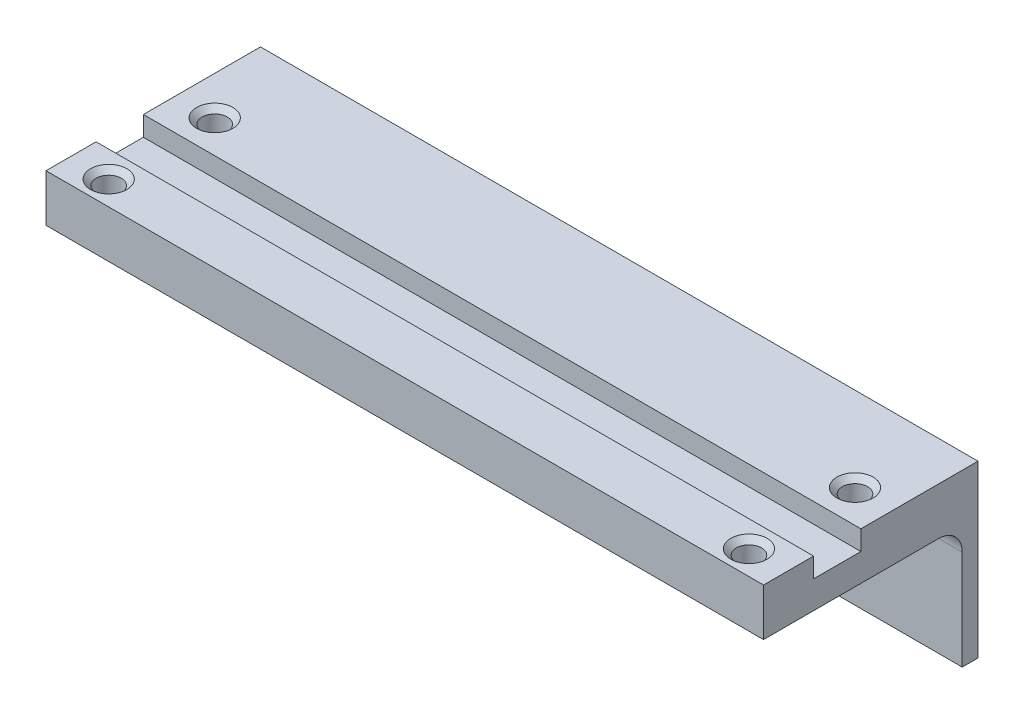
SolidWorks part; units mm, degrees
ref_plane "Front Plane" through (0, 0, 0) normal (0, 0, 1) x (1, 0, 0)
ref_plane "Top Plane" through (0, 0, 0) normal (0, 1, 0) x (1, 0, 0)
ref_plane "Right Plane" through (0, 0, 0) normal (1, 0, 0) x (0, 0, -1)
sketch "Sketch1" plane through (0, 0, 0) normal (0, 1, 0) x (1, 0, 0)
  line L5 (-45.5, 12) -> (45.5, 12)
  line L6 (-45.5, 12) -> (-45.5, -12)
  line L7 (-45.5, -12) -> (45.5, -12)
  line L8 (45.5, 12) -> (45.5, -12)
  line L9 (-45.5, 12) -> (45.5, -12) construction
  line L10 (-45.5, -12) -> (45.5, 12) construction
  point P0 (0, 0)
  dimension "D1" = 91
  dimension "D2" = 24
extrude "Boss-Extrude1" add sketch "Sketch1" along normal blind 4
sketch "Sketch2" plane through (0, 4, 0) normal (0, 1, 0) x (1, 0, 0)
  circle A0 centre (-40.6, 3.5) radius 1.6
  circle A2 centre (-40.6, -9.95) radius 1.6
  circle A3 centre (40.6, 3.5) radius 1.6
  circle A4 centre (40.6, -9.95) radius 1.6
  line B0 (-42.6, 12) -> (-42.6, -12)
  line B1 (-42.6, -12) -> (42.6, -12)
  line B2 (42.6, -12) -> (42.6, 12)
  line B3 (42.6, 12) -> (-42.6, 12)
  line B4 (-42.6, 0) -> (42.6, 0) construction
  line B5 (0, 12) -> (0, -12) construction
  arc B6 (41.75, -9.95) -> (39.45, -9.95) centre (40.6, -9.95) ccw
  arc B7 (39.45, -9.95) -> (41.75, -9.95) centre (40.6, -9.95) ccw
  arc B8 (41.75, 3.5) -> (39.45, 3.5) centre (40.6, 3.5) ccw
  arc B9 (39.45, 3.5) -> (41.75, 3.5) centre (40.6, 3.5) ccw
  arc B10 (11.65, 3.5) -> (9.35, 3.5) centre (10.5, 3.5) ccw
  arc B11 (9.35, 3.5) -> (11.65, 3.5) centre (10.5, 3.5) ccw
  arc B12 (11.65, -9.95) -> (9.35, -9.95) centre (10.5, -9.95) ccw
  arc B13 (9.35, -9.95) -> (11.65, -9.95) centre (10.5, -9.95) ccw
  arc B14 (-39.45, -9.95) -> (-41.75, -9.95) centre (-40.6, -9.95) ccw
  arc B15 (-41.75, -9.95) -> (-39.45, -9.95) centre (-40.6, -9.95) ccw
  arc B16 (-39.45, 3.5) -> (-41.75, 3.5) centre (-40.6, 3.5) ccw
  arc B17 (-41.75, 3.5) -> (-39.45, 3.5) centre (-40.6, 3.5) ccw
  arc B18 (-22.05, -3.65) -> (-20.55, -3.65) centre (-21.3, -3.65) ccw
  arc B19 (-20.55, -3.65) -> (-22.05, -3.65) centre (-21.3, -3.65) ccw
  arc B20 (-9.35, -9.95) -> (-11.65, -9.95) centre (-10.5, -9.95) ccw
  arc B21 (-11.65, -9.95) -> (-9.35, -9.95) centre (-10.5, -9.95) ccw
  arc B22 (20.55, -3.65) -> (22.05, -3.65) centre (21.3, -3.65) ccw
  arc B23 (22.05, -3.65) -> (20.55, -3.65) centre (21.3, -3.65) ccw
  arc B24 (-39.55, -3.65) -> (-38.05, -3.65) centre (-38.8, -3.65) ccw
  arc B25 (-38.05, -3.65) -> (-39.55, -3.65) centre (-38.8, -3.65) ccw
  arc B26 (38.05, -3.65) -> (39.55, -3.65) centre (38.8, -3.65) ccw
  arc B27 (39.55, -3.65) -> (38.05, -3.65) centre (38.8, -3.65) ccw
  arc B28 (-11.65, 3.5) -> (-9.35, 3.5) centre (-10.5, 3.5) ccw
  arc B29 (-9.35, 3.5) -> (-11.65, 3.5) centre (-10.5, 3.5) ccw
  dimension "D1" = 3.2
  dimension "D2" = 3.2
  dimension "D3" = 3.2
  dimension "D4" = 3.2
sketch_block_instance "Block2-2"
sketch_block "Block2"
extrude "Cut-Extrude1" cut sketch "Sketch2" against normal through all contours A2 | A4 | A0 | A3
sketch "Sketch3" plane through (0, 4, 0) normal (0, 1, 0) x (1, 0, 0)
  line L0 (-45.5, 12) -> (-45.5, -12) construction
  line L1 (-45.5, -0.65) -> (45.5, -0.65)
  line L2 (-45.5, -0.65) -> (-45.5, -6.65)
  line L3 (-45.5, -6.65) -> (45.5, -6.65)
  line L4 (45.5, -0.65) -> (45.5, -6.65)
  line L5 (45.5, -12) -> (45.5, 12) construction
  line L6 (-45.5, -3.65) -> (45.5, -3.65) construction
  line L7 (-38.8, -3.65) -> (-21.3, -3.65) construction
  line B0 (-42.6, 12) -> (-42.6, -12)
  line B1 (-42.6, -12) -> (42.6, -12)
  line B2 (42.6, -12) -> (42.6, 12)
  line B3 (42.6, 12) -> (-42.6, 12)
  line B4 (-42.6, 0) -> (42.6, 0) construction
  line B5 (0, 12) -> (0, -12) construction
  arc B6 (41.75, -9.95) -> (39.45, -9.95) centre (40.6, -9.95) ccw
  arc B7 (39.45, -9.95) -> (41.75, -9.95) centre (40.6, -9.95) ccw
  arc B8 (41.75, 3.5) -> (39.45, 3.5) centre (40.6, 3.5) ccw
  arc B9 (39.45, 3.5) -> (41.75, 3.5) centre (40.6, 3.5) ccw
  arc B10 (11.65, 3.5) -> (9.35, 3.5) centre (10.5, 3.5) ccw
  arc B11 (9.35, 3.5) -> (11.65, 3.5) centre (10.5, 3.5) ccw
  arc B12 (11.65, -9.95) -> (9.35, -9.95) centre (10.5, -9.95) ccw
  arc B13 (9.35, -9.95) -> (11.65, -9.95) centre (10.5, -9.95) ccw
  arc B14 (-39.45, -9.95) -> (-41.75, -9.95) centre (-40.6, -9.95) ccw
  arc B15 (-41.75, -9.95) -> (-39.45, -9.95) centre (-40.6, -9.95) ccw
  arc B16 (-39.45, 3.5) -> (-41.75, 3.5) centre (-40.6, 3.5) ccw
  arc B17 (-41.75, 3.5) -> (-39.45, 3.5) centre (-40.6, 3.5) ccw
  arc B18 (-22.05, -3.65) -> (-20.55, -3.65) centre (-21.3, -3.65) ccw
  arc B19 (-20.55, -3.65) -> (-22.05, -3.65) centre (-21.3, -3.65) ccw
  arc B20 (-9.35, -9.95) -> (-11.65, -9.95) centre (-10.5, -9.95) ccw
  arc B21 (-11.65, -9.95) -> (-9.35, -9.95) centre (-10.5, -9.95) ccw
  arc B22 (20.55, -3.65) -> (22.05, -3.65) centre (21.3, -3.65) ccw
  arc B23 (22.05, -3.65) -> (20.55, -3.65) centre (21.3, -3.65) ccw
  arc B24 (-39.55, -3.65) -> (-38.05, -3.65) centre (-38.8, -3.65) ccw
  arc B25 (-38.05, -3.65) -> (-39.55, -3.65) centre (-38.8, -3.65) ccw
  arc B26 (38.05, -3.65) -> (39.55, -3.65) centre (38.8, -3.65) ccw
  arc B27 (39.55, -3.65) -> (38.05, -3.65) centre (38.8, -3.65) ccw
  arc B28 (-11.65, 3.5) -> (-9.35, 3.5) centre (-10.5, 3.5) ccw
  arc B29 (-9.35, 3.5) -> (-11.65, 3.5) centre (-10.5, 3.5) ccw
  dimension "D1" = 6
sketch_block_instance "Block2-3"
extrude "Cut-Extrude2" cut sketch "Sketch3" against normal blind 2.5 contours L2 L1 L4 L3
sketch "Sketch4" plane through (0, 0, -12) normal (0, 0, -1) x (-1, 0, 0)
  line L1 (-45.5, 4) -> (45.5, 4)
  line L2 (-45.5, 4) -> (-45.5, 0)
  line L3 (-45.5, 0) -> (45.5, 0)
  line L4 (45.5, 4) -> (45.5, 0)
extrude "Boss-Extrude2" add sketch "Sketch4" along normal blind 2.2
sketch "Sketch5" plane through (0, 0, 0) normal (0, -1, 0) x (1, 0, 0)
  line L0 (45.5, 12) -> (45.5, -14.2) construction
  line L1 (-45.5, -14.2) -> (45.5, -14.2)
  line L2 (-45.5, -14.2) -> (-45.5, -12.2)
  line L3 (-45.5, -12.2) -> (45.5, -12.2)
  line L4 (45.5, -14.2) -> (45.5, -12.2)
  dimension "D1" = 2
extrude "Boss-Extrude3" add sketch "Sketch5" along normal blind 17.62
sketch "Sketch6" plane through (0, 0, -12.2) normal (0, 0, 1) x (1, 0, 0)
  line L0 (0, -17.62) -> (0, -10.12) construction
  line L1 (45.5, -17.62) -> (-45.5, -17.62) construction
  line L2 (0, -10.12) -> (21.25, -10.12) construction
  line L3 (0, -10.12) -> (-21.25, -10.12) construction
  circle A0 centre (-21.25, -10.12) radius 1.75
  circle A1 centre (0, -10.12) radius 1.75
  circle A2 centre (21.25, -10.12) radius 1.75
  dimension "D4" = 3.5
  dimension "D5" = 3.5
  dimension "D6" = 3.5
  dimension "D1" = 21.25
  dimension "D2" = 21.25
  dimension "D3" = 7.5
extrude "Cut-Extrude3" cut sketch "Sketch6" against normal through all
sketch "Sketch7" plane through (0, 0, 0) normal (0, -1, 0) x (1, 0, 0)
  line L4 (-45.5, -12.2) -> (45.5, -12.2)
  line L5 (45.5, -12.2) -> (45.5, 12)
  line L6 (45.5, 12) -> (-45.5, 12)
  line L7 (-45.5, 12) -> (-45.5, -12.2)
  line L8 (-45.5, -12.2) -> (45.5, -12.2)
  line L9 (45.5, -12.2) -> (45.5, 12)
  line L10 (45.5, 12) -> (-45.5, 12)
  line L11 (-45.5, 12) -> (-45.5, -12.2)
  circle A0 centre (40.6, 9.95) radius 1.6 construction
  circle A1 centre (40.6, -3.5) radius 1.6 construction
  circle A2 centre (-40.6, -3.5) radius 1.6 construction
  circle A3 centre (-40.6, 9.95) radius 1.6 construction
  circle A4 centre (40.6, 9.95) radius 1.6
  circle A5 centre (40.6, -3.5) radius 1.6
  circle A6 centre (-40.6, -3.5) radius 1.6
  circle A7 centre (-40.6, 9.95) radius 1.6
  dimension "D1" = 0
extrude "Boss-Extrude5" add sketch "Sketch7" along normal blind 2
sketch "Sketch8" plane through (0, 0, 12) normal (0, 0, 1) x (1, 0, 0)
  line L6 (45.5, 4) -> (-45.5, 4)
  line L8 (-45.5, 4) -> (-45.5, -2)
  line L9 (-45.5, -2) -> (45.5, -2)
  line L10 (45.5, -2) -> (45.5, 4)
  line L12 (45.5, 4) -> (-45.5, 4)
  line L14 (-45.5, 4) -> (-45.5, -2)
  line L15 (-45.5, -2) -> (45.5, -2)
  line L16 (45.5, -2) -> (45.5, 4)
  dimension "D1" = 0
extrude "Boss-Extrude6" add sketch "Sketch8" along normal blind 1
chamfer "Chamfer1" distance 0.7 angle 45 4 edges at (40.6, 4, 11.55) (-40.6, 4, -1.9) (40.6, 4, -1.9) (-40.6, 4, 11.55)
fillet "Fillet1" radius 3 1 edges at (0, -2, -12.2)
